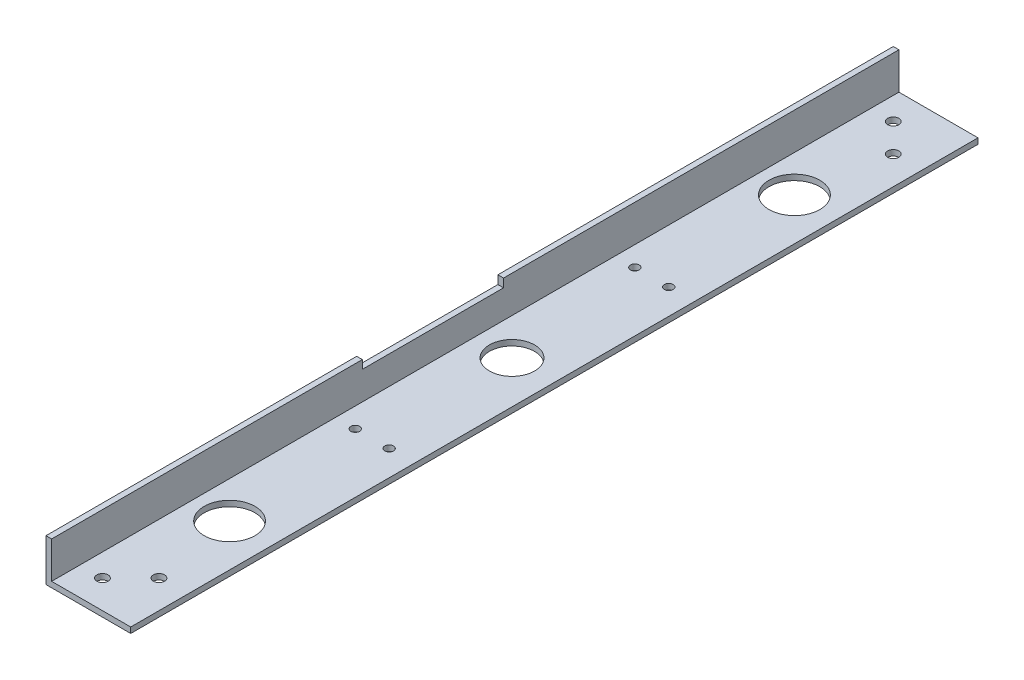
SolidWorks part; units mm, degrees
ref_plane "Front Plane" through (0, 0, 0) normal (0, 0, 1) x (1, 0, 0)
ref_plane "Top Plane" through (0, 0, 0) normal (0, 1, 0) x (1, 0, 0)
ref_plane "Right Plane" through (0, 0, 0) normal (1, 0, 0) x (0, 0, -1)
sketch "Sketch1" plane through (0, 0, 0) normal (0, 0, 1) x (1, 0, 0)
  line L0 (0, 0) -> (0, 25)
  line L1 (0, 25) -> (2, 25)
  line L2 (2, 25) -> (2, 2)
  line L3 (2, 2) -> (30, 2)
  line L4 (30, 2) -> (30, 0)
  line L5 (30, 0) -> (0, 0)
  dimension "D1" = 2
  dimension "D2" = 25
  dimension "D3" = 30
extrude "Boss-Extrude1" add sketch "Sketch1" along normal blind 300
sketch "Sketch2" plane through (0, 2, 0) normal (0, 1, 0) x (1, 0, 0)
  line L0 (30, -150) -> (2, -150) construction
  line L1 (30, -300) -> (30, 0) construction
  line L2 (2, -300) -> (2, 0) construction
  line L3 (30, -10) -> (2, -10) construction
  line L4 (30, -20) -> (2, -20) construction
  line L5 (30, -290) -> (2, -290) construction
  line L6 (30, -280) -> (2, -280) construction
  line L7 (30, -300) -> (2, -300) construction
  line L8 (30, 0) -> (2, 0) construction
  line L9 (10, -290) -> (10, -10) construction
  line L10 (20, -20) -> (20, -280) construction
  circle A0 centre (15, -150) radius 8
  circle A1 centre (10, -10) radius 1.9777
  circle A2 centre (20, -20) radius 1.9777
  circle A3 centre (10, -290) radius 1.9777
  circle A4 centre (20, -280) radius 1.9777
  dimension "D2" = 16
  dimension "D1" = 15
  dimension "D3" = 10
  dimension "D4" = 20
  dimension "D5" = 20
  dimension "D6" = 10
  dimension "D7" = 10
  dimension "D8" = 20
extrude "Cut-Extrude1" cut sketch "Sketch2" against normal blind 10
sketch "Sketch3" plane through (2, 0, 0) normal (1, 0, 0) x (0, 0, -1)
  line L8 (0, 2) -> (0, 25) construction
  line L9 (-300, 25) -> (0, 25)
  line L13 (-300, 25) -> (-300, 15)
  line L14 (-300, 15) -> (0, 15)
  line L15 (0, 25) -> (0, 15)
  dimension "D5" = 15
extrude "Cut-Extrude2" cut sketch "Sketch3" against normal blind 10
sketch "Sketch4" plane through (2, 0, 0) normal (1, 0, 0) x (0, 0, -1)
  line L0 (-300, 15) -> (0, 15) construction
  line L1 (-140, 15) -> (-190, 15)
  line L2 (-140, 15) -> (-140, 12)
  line L3 (-140, 12) -> (-190, 12)
  line L4 (-190, 15) -> (-190, 12)
  dimension "D1" = 3
  dimension "D2" = 140
  dimension "D3" = 50
extrude "Cut-Extrude3" cut sketch "Sketch4" against normal blind 10
sketch "Sketch5" plane through (0, 0, 0) normal (0, -1, 0) x (1, 0, 0)
  circle A0 centre (21, 199.5) radius 1.55
  circle A1 centre (9, 199.5) radius 1.55
  circle A2 centre (21, 100.5) radius 1.55
  circle A3 centre (9, 100.5) radius 1.55
extrude "Cut-Extrude4" cut sketch "Sketch5" against normal blind 273
sketch "Sketch6" plane through (0, 0, 0) normal (0, -1, 0) x (1, 0, 0)
  circle A0 centre (15, 250) radius 9
  circle A1 centre (15, 50) radius 9
  circle A2 centre (-238, 50) radius 9
  circle A3 centre (-238, 250) radius 9
extrude "Cut-Extrude5" cut sketch "Sketch6" against normal blind 5
